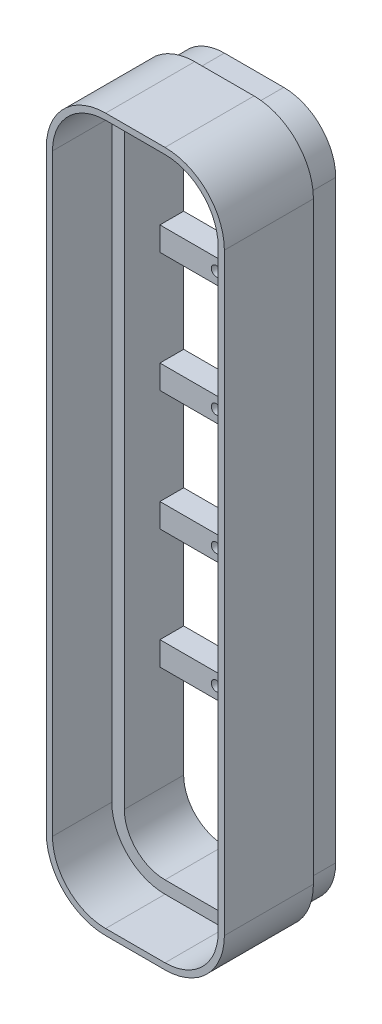
SolidWorks part; units mm, degrees
ref_plane "Front Plane" through (0, 0, 0) normal (0, 0, 1) x (1, 0, 0)
ref_plane "Top Plane" through (0, 0, 0) normal (0, 1, 0) x (1, 0, 0)
ref_plane "Right Plane" through (0, 0, 0) normal (1, 0, 0) x (0, 0, -1)
sketch "Sketch1" plane through (0, 0, 0) normal (0, 0, 1) x (1, 0, 0)
  line L1 (-19.05, -76.2) -> (19.05, -76.2)
  line L2 (-19.05, -76.2) -> (-19.05, 76.2)
  line L3 (-19.05, 76.2) -> (19.05, 76.2)
  line L4 (19.05, -76.2) -> (19.05, 76.2)
  line L5 (-19.05, -76.2) -> (19.05, 76.2) construction
  line L6 (-19.05, 76.2) -> (19.05, -76.2) construction
  point P0 (0, 0)
  dimension "D1" = 38.1
  dimension "D2" = 152.4
extrude "Boss-Extrude1" add sketch "Sketch1" along normal mid plane 25.4
fillet "Fillet1" radius 12.7 4 edges at (19.05, -76.2, 0) (-19.05, -76.2, 0) (19.05, 76.2, 0) (-19.05, 76.2, 0)
sketch "Sketch2" plane through (0, 0, 12.7) normal (0, 0, 1) x (1, 0, 0)
  line L0 (-17.5992, 63.5) -> (-17.5992, -63.5)
  line L1 (-6.35, -74.7492) -> (6.35, -74.7492)
  line L2 (17.5992, -63.5) -> (17.5992, 63.5)
  line L3 (6.35, 74.7492) -> (-6.35, 74.7492)
  line L4 (-6.35, -76.2) -> (6.35, -76.2)
  line L5 (19.05, -63.5) -> (19.05, 63.5)
  line L6 (6.35, 76.2) -> (-6.35, 76.2)
  line L7 (-19.05, 63.5) -> (-19.05, -63.5)
  line L8 (-6.35, -76.2) -> (6.35, -76.2) construction
  line L9 (19.05, -63.5) -> (19.05, 63.5) construction
  line L10 (6.35, 76.2) -> (-6.35, 76.2) construction
  line L11 (-19.05, 63.5) -> (-19.05, -63.5) construction
  arc A0 (-6.35, 74.7492) -> (-17.5992, 63.5) centre (-6.35, 63.5) ccw
  arc A1 (-17.5992, -63.5) -> (-6.35, -74.7492) centre (-6.35, -63.5) ccw
  arc A2 (6.35, -74.7492) -> (17.5992, -63.5) centre (6.35, -63.5) ccw
  arc A3 (17.5992, 63.5) -> (6.35, 74.7492) centre (6.35, 63.5) ccw
  arc A4 (6.35, -76.2) -> (19.05, -63.5) centre (6.35, -63.5) ccw
  arc A5 (19.05, 63.5) -> (6.35, 76.2) centre (6.35, 63.5) ccw
  arc A6 (-6.35, 76.2) -> (-19.05, 63.5) centre (-6.35, 63.5) ccw
  arc A7 (-19.05, -63.5) -> (-6.35, -76.2) centre (-6.35, -63.5) ccw
  arc A8 (6.35, -76.2) -> (19.05, -63.5) centre (6.35, -63.5) ccw construction
  arc A9 (19.05, 63.5) -> (6.35, 76.2) centre (6.35, 63.5) ccw construction
  arc A10 (-6.35, 76.2) -> (-19.05, 63.5) centre (-6.35, 63.5) ccw construction
  arc A11 (-19.05, -63.5) -> (-6.35, -76.2) centre (-6.35, -63.5) ccw construction
  dimension "D1" = 0
  dimension "D2" = 1.4508
extrude "Cut-Extrude1" cut sketch "Sketch2" against normal through all
sketch "Sketch3" plane through (0, 0, -12.7) normal (0, 0, -1) x (-1, 0, 0)
  line L0 (6.35, -74.7492) -> (-6.35, -74.7492) construction
  line L1 (17.5992, 63.5) -> (17.5992, -63.5) construction
  line L2 (-6.35, 74.7492) -> (6.35, 74.7492) construction
  line L3 (-17.5992, -63.5) -> (-17.5992, 63.5) construction
  line L4 (6.35, -74.7492) -> (-6.35, -74.7492)
  line L5 (17.5992, 63.5) -> (17.5992, -63.5)
  line L6 (-6.35, 74.7492) -> (6.35, 74.7492)
  line L7 (-17.5992, -63.5) -> (-17.5992, 63.5)
  arc A0 (-17.5992, -63.5) -> (-6.35, -74.7492) centre (-6.35, -63.5) ccw construction
  arc A1 (6.35, -74.7492) -> (17.5992, -63.5) centre (6.35, -63.5) ccw construction
  arc A2 (17.5992, 63.5) -> (6.35, 74.7492) centre (6.35, 63.5) ccw construction
  arc A3 (-6.35, 74.7492) -> (-17.5992, 63.5) centre (-6.35, 63.5) ccw construction
  arc A4 (-17.5992, -63.5) -> (-6.35, -74.7492) centre (-6.35, -63.5) ccw
  arc A5 (6.35, -74.7492) -> (17.5992, -63.5) centre (6.35, -63.5) ccw
  arc A6 (17.5992, 63.5) -> (6.35, 74.7492) centre (6.35, 63.5) ccw
  arc A7 (-6.35, 74.7492) -> (-17.5992, 63.5) centre (-6.35, 63.5) ccw
extrude "Extrude-Thin1" add sketch "Sketch3" against normal blind 12.7 thin
sketch "Sketch4" plane through (0, 0, -12.7) normal (0, 0, -1) x (-1, 0, 0)
  line L0 (6.35, -76.2) -> (-6.35, -76.2) construction
  line L1 (19.05, 63.5) -> (19.05, -63.5) construction
  line L2 (-19.05, -63.5) -> (-19.05, 63.5) construction
  line L3 (-6.35, 76.2) -> (6.35, 76.2) construction
  line L4 (6.35, -76.2) -> (-6.35, -76.2)
  line L5 (19.05, 63.5) -> (19.05, -63.5)
  line L6 (-19.05, -63.5) -> (-19.05, 63.5)
  line L7 (-6.35, 76.2) -> (6.35, 76.2)
  line L8 (-17.5992, -63.5) -> (-17.5992, 63.5)
  line L9 (-6.35, 74.7492) -> (6.35, 74.7492)
  line L10 (17.5992, 63.5) -> (17.5992, -63.5)
  line L11 (6.35, -74.7492) -> (-6.35, -74.7492)
  arc A0 (-19.05, -63.5) -> (-6.35, -76.2) centre (-6.35, -63.5) ccw construction
  arc A1 (6.35, -76.2) -> (19.05, -63.5) centre (6.35, -63.5) ccw construction
  arc A2 (19.05, 63.5) -> (6.35, 76.2) centre (6.35, 63.5) ccw construction
  arc A3 (-6.35, 76.2) -> (-19.05, 63.5) centre (-6.35, 63.5) ccw construction
  arc A4 (-19.05, -63.5) -> (-6.35, -76.2) centre (-6.35, -63.5) ccw
  arc A5 (6.35, -76.2) -> (19.05, -63.5) centre (6.35, -63.5) ccw
  arc A6 (19.05, 63.5) -> (6.35, 76.2) centre (6.35, 63.5) ccw
  arc A7 (-6.35, 76.2) -> (-19.05, 63.5) centre (-6.35, 63.5) ccw
  arc A8 (-6.35, 74.7492) -> (-17.5992, 63.5) centre (-6.35, 63.5) ccw
  arc A9 (17.5992, 63.5) -> (6.35, 74.7492) centre (6.35, 63.5) ccw
  arc A10 (6.35, -74.7492) -> (17.5992, -63.5) centre (6.35, -63.5) ccw
  arc A11 (-17.5992, -63.5) -> (-6.35, -74.7492) centre (-6.35, -63.5) ccw
  dimension "D1" = 1.4508
extrude "Cut-Extrude2" cut sketch "Sketch4" against normal blind 6.35
ref_plane "Plane1" through (0, 0, -7.62) normal (0, 0, -1) x (-1, 0, 0)
sketch "Sketch6" plane through (0, 0, -7.62) normal (0, 0, -1) x (-1, 0, 0)
  line L0 (17.5992, -63.5) -> (17.5992, 63.5) construction
  line L1 (-17.5992, 35.8915) -> (17.5992, 35.8915)
  line L2 (-17.5992, 35.8915) -> (-17.5992, 40.9715)
  line L3 (-17.5992, 40.9715) -> (17.5992, 40.9715)
  line L4 (17.5992, 35.8915) -> (17.5992, 40.9715)
  line L5 (-17.5992, 35.8915) -> (17.5992, 40.9715) construction
  line L6 (-17.5992, 40.9715) -> (17.5992, 35.8915) construction
  line L7 (17.5992, -63.5) -> (17.5992, 63.5) construction
  line L8 (-17.5992, 10.299) -> (17.5992, 10.299)
  line L9 (-17.5992, 10.299) -> (-17.5992, 15.379)
  line L10 (-17.5992, 15.379) -> (17.5992, 15.379)
  line L11 (17.5992, 10.299) -> (17.5992, 15.379)
  line L12 (-17.5992, 10.299) -> (17.5992, 15.379) construction
  line L13 (-17.5992, 15.379) -> (17.5992, 10.299) construction
  line L14 (-17.5992, 63.5) -> (-17.5992, -63.5) construction
  line L15 (-17.5992, -15.3585) -> (17.5992, -15.3585)
  line L16 (-17.5992, -15.3585) -> (-17.5992, -10.2785)
  line L17 (-17.5992, -10.2785) -> (17.5992, -10.2785)
  line L18 (17.5992, -15.3585) -> (17.5992, -10.2785)
  line L19 (-17.5992, -15.3585) -> (17.5992, -10.2785) construction
  line L20 (-17.5992, -10.2785) -> (17.5992, -15.3585) construction
  line L21 (-17.5992, -40.951) -> (17.5992, -40.951)
  line L22 (-17.5992, -40.951) -> (-17.5992, -35.871)
  line L23 (-17.5992, -35.871) -> (17.5992, -35.871)
  line L24 (17.5992, -40.951) -> (17.5992, -35.871)
  line L25 (-17.5992, -40.951) -> (17.5992, -35.871) construction
  line L26 (-17.5992, -35.871) -> (17.5992, -40.951) construction
  circle A0 centre (3.0157, -38.411) radius 1.0543 construction
  circle A1 centre (3.0157, -12.8185) radius 1.0543 construction
  circle A2 centre (3.0157, 12.839) radius 1.0543 construction
  circle A3 centre (3.0157, 38.4315) radius 1.0543 construction
  circle A4 centre (3.0157, -38.411) radius 1.0543
  circle A5 centre (3.0157, -12.8185) radius 1.0543
  circle A6 centre (3.0157, 12.839) radius 1.0543
  circle A7 centre (3.0157, 38.4315) radius 1.0543
  point P12 (0, 38.4315)
  point P19 (0, 12.839)
  point P26 (0, -12.8185)
  point P31 (0, -38.411)
  dimension "D1" = 5.08
extrude "Boss-Extrude2" add sketch "Sketch6" along normal up to surface (5.08 mm away) up to face at (0, 0, -12.7)
sketch "Sketch7" plane through (0, 0, -12.7) normal (0, 0, -1) x (-1, 0, 0)
  line L0 (-6.35, -74.7492) -> (6.35, -74.7492) construction
  line L1 (6.35, 74.7492) -> (-6.35, 74.7492) construction
  line L2 (17.5992, -63.5) -> (17.5992, 63.5) construction
  line L3 (-17.5992, 63.5) -> (-17.5992, -63.5) construction
  line L4 (-6.35, -74.7492) -> (6.35, -74.7492)
  line L5 (6.35, 74.7492) -> (-6.35, 74.7492)
  line L6 (17.5992, -63.5) -> (17.5992, 63.5)
  line L7 (-17.5992, 63.5) -> (-17.5992, -63.5)
  arc A0 (6.35, -74.7492) -> (17.5992, -63.5) centre (6.35, -63.5) ccw construction
  arc A1 (-17.5992, -63.5) -> (-6.35, -74.7492) centre (-6.35, -63.5) ccw construction
  arc A2 (17.5992, 63.5) -> (6.35, 74.7492) centre (6.35, 63.5) ccw construction
  arc A3 (-6.35, 74.7492) -> (-17.5992, 63.5) centre (-6.35, 63.5) ccw construction
  arc A4 (6.35, -74.7492) -> (17.5992, -63.5) centre (6.35, -63.5) ccw
  arc A5 (-17.5992, -63.5) -> (-6.35, -74.7492) centre (-6.35, -63.5) ccw
  arc A6 (17.5992, 63.5) -> (6.35, 74.7492) centre (6.35, 63.5) ccw
  arc A7 (-6.35, 74.7492) -> (-17.5992, 63.5) centre (-6.35, 63.5) ccw
extrude "Clearance 1" cut sketch "Sketch7" against normal up to surface (6.35 mm away) thin up to face at (0, 0, -6.35) thin type one direction reverse wall 0.127
sketch "Sketch8" plane through (0, 0, 12.7) normal (0, 0, 1) x (1, 0, 0)
  line L0 (-6.35, -74.7492) -> (6.35, -74.7492) construction
  line L1 (17.5992, -63.5) -> (17.5992, 63.5) construction
  line L2 (-17.5992, 63.5) -> (-17.5992, -63.5) construction
  line L3 (6.35, 74.7492) -> (-6.35, 74.7492) construction
  line L4 (-6.35, -74.7492) -> (6.35, -74.7492)
  line L5 (17.5992, -63.5) -> (17.5992, 63.5)
  line L6 (-17.5992, 63.5) -> (-17.5992, -63.5)
  line L7 (6.35, 74.7492) -> (-6.35, 74.7492)
  arc A0 (-17.5992, -63.5) -> (-6.35, -74.7492) centre (-6.35, -63.5) ccw construction
  arc A1 (6.35, -74.7492) -> (17.5992, -63.5) centre (6.35, -63.5) ccw construction
  arc A2 (17.5992, 63.5) -> (6.35, 74.7492) centre (6.35, 63.5) ccw construction
  arc A3 (-6.35, 74.7492) -> (-17.5992, 63.5) centre (-6.35, 63.5) ccw construction
  arc A4 (-17.5992, -63.5) -> (-6.35, -74.7492) centre (-6.35, -63.5) ccw
  arc A5 (6.35, -74.7492) -> (17.5992, -63.5) centre (6.35, -63.5) ccw
  arc A6 (17.5992, 63.5) -> (6.35, 74.7492) centre (6.35, 63.5) ccw
  arc A7 (-6.35, 74.7492) -> (-17.5992, 63.5) centre (-6.35, 63.5) ccw
extrude "Cut-Extrude-Thin2" cut sketch "Sketch8" against normal up to surface (12.7 mm away) thin
